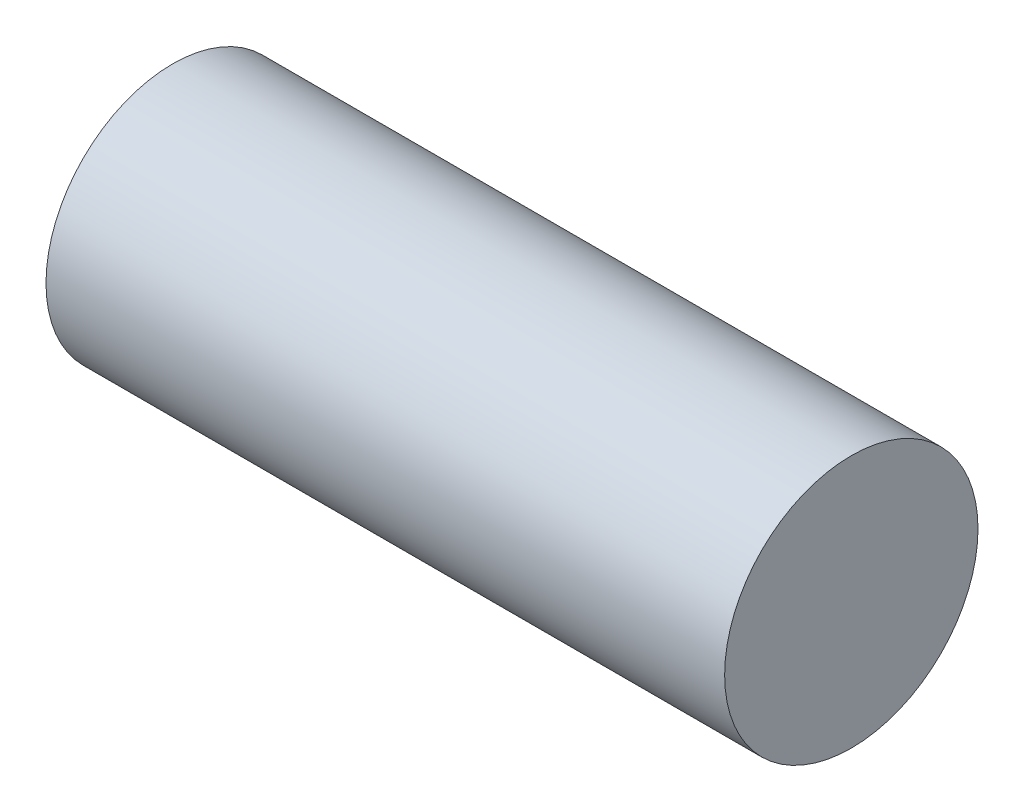
SolidWorks part; units mm, degrees
ref_plane "Alzado" through (0, 0, 0) normal (0, 0, 1) x (1, 0, 0)
ref_plane "Planta" through (0, 0, 0) normal (0, 1, 0) x (1, 0, 0)
ref_plane "Vista lateral" through (0, 0, 0) normal (1, 0, 0) x (0, 0, -1)
sketch "Croquis1" plane through (0, 0, 0) normal (1, 0, 0) x (0, 0, -1)
  circle A0 centre (0, 0) radius 28
  dimension "D1" = 56
extrude "Saliente-Extruir1" add sketch "Croquis1" along normal blind 150
